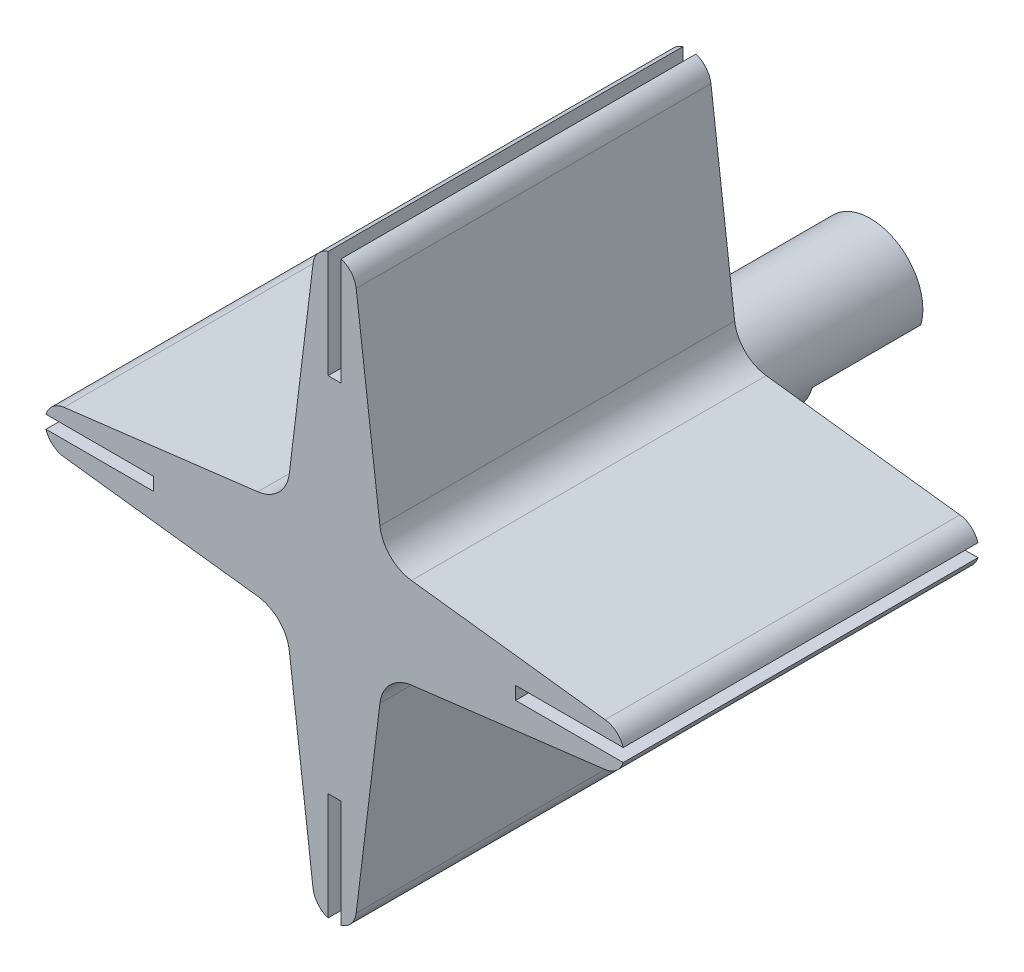
SolidWorks part; units mm, degrees
ref_plane "Front Plane" through (0, 0, 0) normal (0, 0, 1) x (1, 0, 0)
ref_plane "Top Plane" through (0, 0, 0) normal (0, 1, 0) x (1, 0, 0)
ref_plane "Right Plane" through (0, 0, 0) normal (1, 0, 0) x (0, 0, -1)
sketch "Sketch1" plane through (0, 0, 0) normal (0, 0, 1) x (1, 0, 0)
  line L0 (-6.7313, 6.7313) -> (-2.9777, 37.3649)
  line L1 (2.9777, 37.3649) -> (6.7313, 6.7313)
  line L2 (6.7313, 6.7313) -> (37.3649, 2.9777)
  line L3 (37.3649, -2.9777) -> (6.7313, -6.7313)
  line L4 (6.7313, -6.7313) -> (2.9777, -37.3649)
  line L5 (-2.9777, -37.3649) -> (-6.7313, -6.7313)
  line L6 (-6.7313, -6.7313) -> (-37.3649, -2.9777)
  line L7 (-37.3649, 2.9777) -> (-6.7313, 6.7313)
  circle A0 centre (0, 0) radius 50 construction
  circle A1 centre (0, 0) radius 7.5
  arc A2 (-2.9777, 37.3649) -> (2.9777, 37.3649) centre (0, 37) cw
  arc A3 (37.3649, 2.9777) -> (37.3649, -2.9777) centre (37, 0) cw
  arc A4 (2.9777, -37.3649) -> (-2.9777, -37.3649) centre (0, -37) cw
  arc A5 (-37.3649, -2.9777) -> (-37.3649, 2.9777) centre (-37, 0) cw
  point P8 (0, 50)
  point P11 (0, 40)
  point P13 (0, 0)
  point P29 (0, 0)
  dimension "D1" = 100
  dimension "D2" = 15
  dimension "D3" = 40
  dimension "D4" = 3
  dimension "D5" = 4
extrude "Boss-Extrude1" add sketch "Sketch1" along normal blind 49
fillet "Fillet1" radius 5 4 edges at (6.7313, -6.7313, 24.5) (-6.7313, -6.7313, 24.5) (-6.7313, 6.7313, 24.5) (6.7313, 6.7313, 24.5)
sketch "Sketch2" plane through (0, 0, 0) normal (0, 0, -1) x (-1, 0, 0)
  circle A0 centre (0, 0) radius 7.25
  dimension "D1" = 14.5
extrude "Boss-Extrude2" add sketch "Sketch2" along normal blind 25
sketch "Sketch3" plane through (0, 0, -25) normal (0, 0, -1) x (-1, 0, 0)
  line L0 (6.9687, -2) -> (-6.9687, -2)
  circle A0 centre (0, 0) radius 7.25 construction
  arc A1 (6.9687, -2) -> (-6.9687, -2) centre (0, 0) cw
  circle M2 centre (0, 0) radius 7.25
  dimension "D1" = 2
extrude "Cut-Extrude1" cut sketch "Sketch3" against normal blind 15 contours L0 M2
sketch "Sketch4" plane through (0, 0, 49) normal (0, 0, 1) x (1, 0, 0)
  line L0 (0, 0) -> (0, 40) construction
  line L1 (50, 0.8938) -> (25, 0.8938)
  line L2 (-0.8937, 50) -> (0.8937, 50)
  line L3 (-0.8937, 50) -> (-0.8937, 25)
  line L4 (-0.8937, 25) -> (0.8937, 25)
  line L5 (0.8937, 50) -> (0.8937, 25)
  line L6 (50, -0.8937) -> (25, -0.8937)
  line L7 (50, 0.8938) -> (50, -0.8937)
  line L8 (25, 0.8938) -> (25, -0.8937)
  line L9 (0.8938, -50) -> (0.8938, -25)
  line L10 (-0.8937, -50) -> (-0.8937, -25)
  line L11 (0.8938, -50) -> (-0.8937, -50)
  line L12 (0.8938, -25) -> (-0.8937, -25)
  line L13 (-50, -0.8938) -> (-25, -0.8938)
  line L14 (-50, 0.8937) -> (-25, 0.8937)
  line L15 (-50, -0.8938) -> (-50, 0.8937)
  line L16 (-25, -0.8938) -> (-25, 0.8937)
  arc A0 (2.9777, 37.3649) -> (-2.9777, 37.3649) centre (0, 37) ccw construction
  point P10 (0, 50)
  point P26 (0, 0)
  dimension "D1" = 1.7875
  dimension "D2" = 15
  dimension "D3" = 10
  dimension "D4" = 4
extrude "Cut-Extrude2" cut sketch "Sketch4" against normal up to surface (49 mm away) up to face at (7.25, 0, 0)
